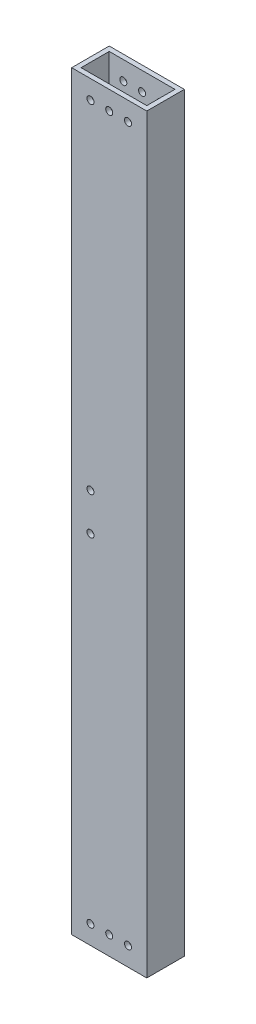
SolidWorks part; units mm, degrees
ref_plane "Front Plane" through (0, 0, 0) normal (0, 0, 1) x (1, 0, 0)
ref_plane "Top Plane" through (0, 0, 0) normal (0, 1, 0) x (1, 0, 0)
ref_plane "Right Plane" through (0, 0, 0) normal (1, 0, 0) x (0, 0, -1)
sketch "Sketch1" plane through (0, 0, 0) normal (0, 1, 0) x (1, 0, 0)
  line L1 (-25.4, 12.7) -> (25.4, 12.7)
  line L2 (-25.4, 12.7) -> (-25.4, -12.7)
  line L3 (-25.4, -12.7) -> (25.4, -12.7)
  line L4 (25.4, 12.7) -> (25.4, -12.7)
  line L5 (0, -12.7) -> (0, 12.7) construction
  line L6 (-25.4, 0) -> (25.4, 0) construction
  point P0 (0, 0)
  dimension "D1" = 50.8
  dimension "D2" = 25.4
extrude "Boss-Extrude1" add sketch "Sketch1" along normal mid plane 508
shell "Shell1" thickness 3.175
sketch "Sketch2" plane through (0, 0, -12.7) normal (0, 0, -1) x (-1, 0, 0)
  line L0 (12.7, 12.7) -> (12.7, -12.7) construction
  line L1 (25.4, 254) -> (25.4, -254) construction
  circle A0 centre (12.7, -12.7) radius 2.3813
  circle A1 centre (12.7, 12.7) radius 2.3813
  point P7 (12.7, 0)
  dimension "D2" = 4.7625
  dimension "D1" = 12.7
  dimension "D3" = 25.4
extrude "Cut-Extrude1" cut sketch "Sketch2" against normal through all
sketch "Sketch3" plane through (0, 0, -12.7) normal (0, 0, -1) x (-1, 0, 0)
  line L0 (12.7, -241.3) -> (-12.7, -241.3) construction
  line L1 (-25.4, -254) -> (25.4, -254) construction
  line L2 (0, 0) -> (-50000, 0) construction
  line L3 (12.7, 241.3) -> (-12.7, 241.3) construction
  circle A0 centre (0, -241.3) radius 2.3812
  circle A1 centre (12.7, -241.3) radius 2.3813
  circle A2 centre (-12.7, -241.3) radius 2.3813
  circle A3 centre (12.7, 12.7) radius 2.3813 construction
  circle A4 centre (-12.7, 241.3) radius 2.3813
  circle A5 centre (12.7, 241.3) radius 2.3813
  circle A6 centre (0, 241.3) radius 2.3812
  point P9 (0, -241.3)
  point P21 (0, 241.3)
  dimension "D1" = 12.7
  dimension "D2" = 25.4
extrude "Cut-Extrude2" cut sketch "Sketch3" against normal through all
